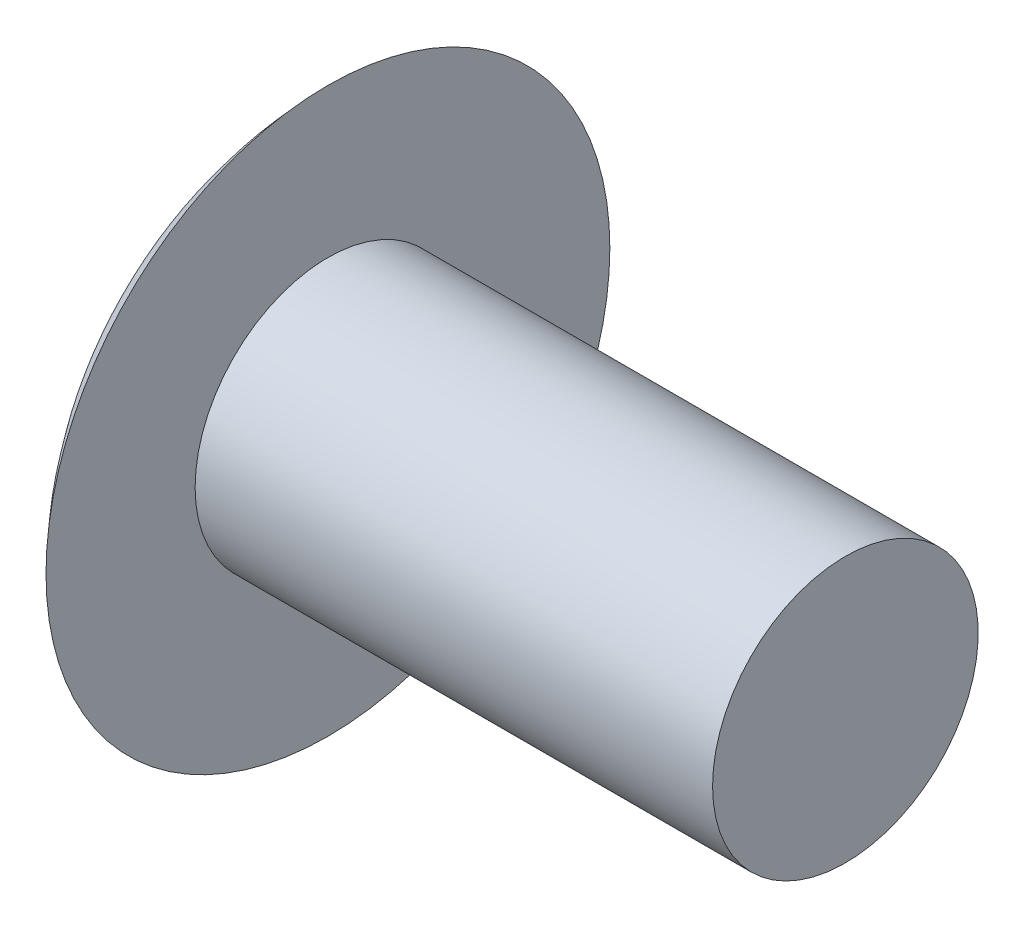
SolidWorks part; units mm, degrees
material "51"
ref_plane "前视基准面" through (0, 0, 0) normal (0, 0, 1) x (1, 0, 0)
ref_plane "上视基准面" through (0, 0, 0) normal (0, 1, 0) x (1, 0, 0)
ref_plane "右视基准面" through (0, 0, 0) normal (1, 0, 0) x (0, 0, -1)
sketch "草图1" plane through (0, 0, 0) normal (0, 1, 0) x (1, 0, 0)
  line L2 (0, 0) -> (51.1784, 0) construction
  line L4 (25, -3.269) -> (25, -1.54)
  line L5 (25, -1.54) -> (31, -1.54)
  line L6 (31, -1.54) -> (31, 0)
  line L8 (23.7, 0) -> (31, 0)
  arc A0 (23.7, 0) -> (25, -3.269) centre (28.46, 0) ccw
  dimension "D3" = 6
  dimension "D6" = 1.54
  dimension "D2" = 3.269
  dimension "D4" = 25
  dimension "D5" = 1.3
revolve "旋转1" add sketch "草图1" angle 360 about L2
equation "\"d\"= 3.08"
equation "\"dk\"= 6.3"
equation "\"k\"= 1.3"
equation "\"dm\"= 2.05"
equation "\"p\"= 25"
equation "\"b\"= 4 + \"l\""
equation "\"l\"= 6"
equation "\"D3@草图1\"=\"l\""
equation "\"D4@草图1\"=\"p\""
equation "\"D5@草图1\"=\"k\""
